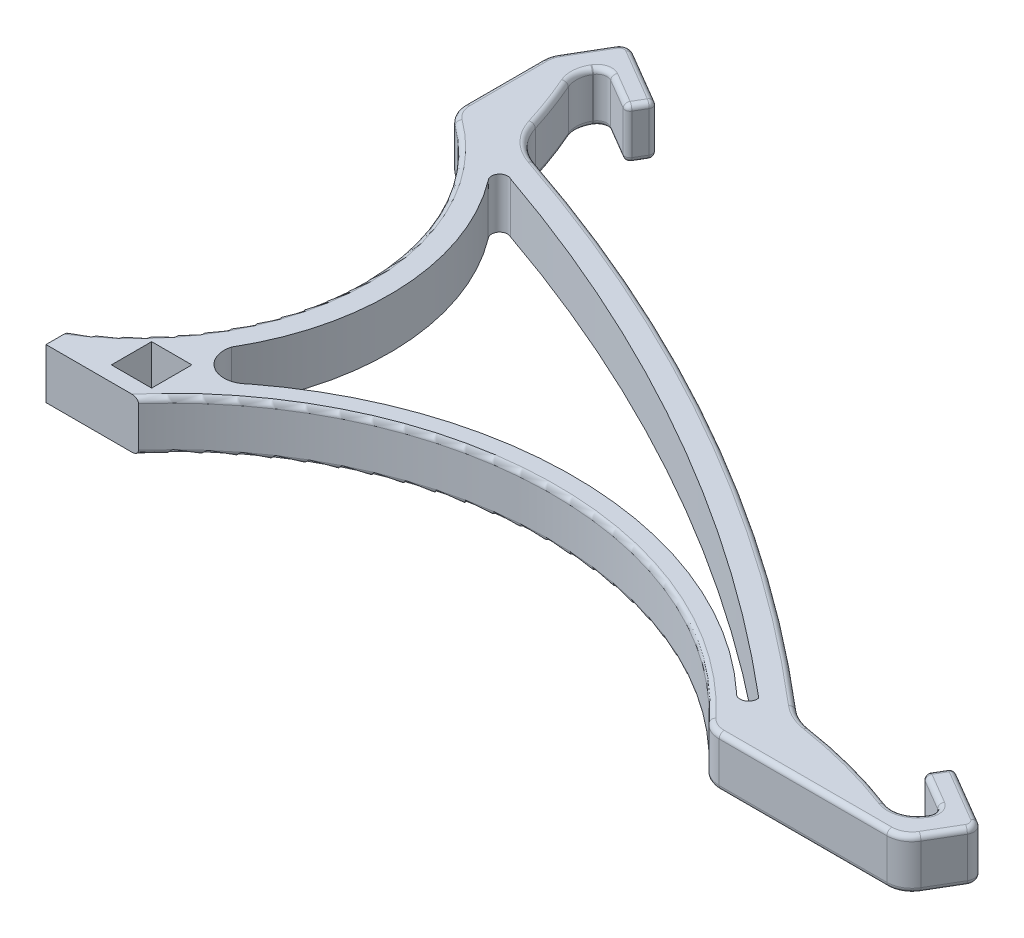
SolidWorks part; units mm, degrees
ref_plane "Front Plane" through (0, 0, 0) normal (0, 0, 1) x (1, 0, 0)
ref_plane "Top Plane" through (0, 0, 0) normal (0, 1, 0) x (1, 0, 0)
ref_plane "Right Plane" through (0, 0, 0) normal (1, 0, 0) x (0, 0, -1)
sketch "Sketch1" plane through (0, 0, 0) normal (0, 1, 0) x (1, 0, 0)
  line L0 (-82.5, 52.5) -> (87.5, -47.5)
  line L2 (-82.5, 52.5) -> (-82.5, -47.5)
  line L3 (-82.5, -47.5) -> (87.5, -47.5)
  point P0 (0, 0)
  dimension "D1" = 170
  dimension "D2" = 100
extrude "Boss-Extrude1" add sketch "Sketch1" along normal blind 10
sketch "Sketch2" plane through (0, 10, 0) normal (0, 1, 0) x (1, 0, 0)
  line L0 (28.4245, 45.2593) -> (-47.6285, -84.0308) construction
  line L1 (-7.5, -97.5) -> (-7.5, 22.4346) construction
  line L2 (-107.5, -4.7657) -> (210.8168, -7.7793) construction
  line L3 (-72.5, 46.6176) -> (-72.5, 42.261)
  line L4 (87.5, -47.5) -> (-82.5, 52.5) construction
  line L5 (70.501, -37.5006) -> (60.6028, -37.4952)
  line L6 (-82.5, -47.5) -> (87.5, -47.5) construction
  line L8 (-82.5, 52.5) -> (-82.5, -47.5) construction
  line L11 (70.501, -37.5006) -> (-72.5, 46.6176)
  line L12 (49.1121, -47.5) -> (-64.1121, -47.5)
  line L13 (-82.5, -42.735) -> (-82.5, 33.2036)
  arc A0 (-65.6807, 32.7803) -> (-72.5, 42.261) centre (-62.5, 42.261) cw
  arc A1 (54.1101, -35.0961) -> (60.6028, -37.4952) centre (60.6083, -27.4952) ccw
  arc A2 (-54.7539, -22.0523) -> (-51.8167, -24.3855) centre (-52.8534, -22.6752) ccw
  arc A5 (-55.6068, -34.1618) -> (-63.6168, -29.4695) centre (-59.0265, -30.8165) cw
  arc A6 (49.1121, -47.5) -> (-64.1121, -47.5) centre (-7.5, -97.5) ccw
  arc A7 (-82.5, -42.735) -> (-82.5, 33.2036) centre (-107.5, -4.7657) ccw
  arc A11 (49.1744, -37.4931) -> (46.162, -38.8845) centre (47.5173, -37.8621) cw
  arc A12 (54.1101, -35.0961) -> (-65.6807, 32.7803) centre (-180.5315, -309.5568) ccw
  arc A14 (-64.8707, 27.2014) -> (-66.8024, 24.71) centre (-65.6394, 25.8028) ccw
  arc A15 (49.1744, -37.4931) -> (-64.8707, 27.2014) centre (-180.5315, -309.5568) ccw
  arc A16 (-66.8024, 24.71) -> (-63.6168, -29.4695) centre (-105.788, -4.7657) cw
  arc A17 (-55.6068, -34.1618) -> (46.162, -38.8845) centre (-7.5, -96.3777) cw
  point P2 (54.1121, -47.5)
  point P3 (-69.1121, -47.5)
  point P9 (-82.5, 38.2036)
  point P25 (-82.5, -47.735)
  dimension "D1" = 5
  dimension "D2" = 5
  dimension "D3" = 2
  dimension "D4" = 90
  dimension "D11" = 10
  dimension "D5" = 97.95
  dimension "D6" = 100
  dimension "D7" = 50
  dimension "D8" = 5
  dimension "D9" = 5
extrude "Cut-Extrude1" cut sketch "Sketch2" against normal through all
sketch "Sketch3" plane through (0, 10, 0) normal (0, 1, 0) x (1, 0, 0)
  line L0 (87.5, -47.5) -> (92.3674, -39.2254)
  line L1 (-82.5, 52.5) -> (-77.6133, 60.8074)
  line L2 (87.5, -47.5) -> (70.501, -37.5006) construction
  line L3 (91.6576, -36.4875) -> (81.3144, -30.4033)
  line L4 (78.6778, -32.913) -> (79.9454, -30.7582)
  line L5 (-74.8754, 61.5172) -> (-64.5322, 55.4329)
  line L6 (79.0328, -34.282) -> (85.0663, -37.8311)
  line L7 (85.7761, -40.569) -> (83.1903, -44.9649)
  line L8 (83.1903, -44.9649) -> (87.5, -47.5)
  line L9 (-64.1773, 54.064) -> (-65.4448, 51.9092)
  line L10 (-66.8138, 51.5542) -> (-72.8473, 55.1034)
  line L11 (-75.5852, 54.3936) -> (-78.1903, 49.9649)
  line L12 (-72.5, 46.6176) -> (-82.5, 52.5) construction
  line L13 (-78.1903, 49.9649) -> (-82.5, 52.5)
  arc A0 (92.3674, -39.2254) -> (91.6576, -36.4875) centre (90.6435, -38.2114) ccw
  arc A1 (85.0663, -37.8311) -> (85.7761, -40.569) centre (84.0523, -39.555) cw
  arc A2 (79.0328, -34.282) -> (78.6778, -32.913) centre (79.5398, -33.4201) cw
  arc A3 (81.3144, -30.4033) -> (79.9454, -30.7582) centre (80.8073, -31.2652) ccw
  arc A4 (-72.8473, 55.1034) -> (-75.5852, 54.3936) centre (-73.8614, 53.3795) ccw
  arc A5 (-77.6133, 60.8074) -> (-74.8754, 61.5172) centre (-75.8895, 59.7933) cw
  arc A6 (-64.5322, 55.4329) -> (-64.1773, 54.064) centre (-65.0392, 54.571) cw
  arc A7 (-65.4448, 51.9092) -> (-66.8138, 51.5542) centre (-66.3068, 52.4162) cw
  point P11 (93.3814, -37.5016)
  point P20 (80.4524, -29.8963)
  point P32 (-76.5993, 62.5312)
  point P35 (-63.6703, 54.9259)
  point P38 (-65.9519, 51.0472)
  dimension "D5" = 2
  dimension "D6" = 1
  dimension "D22" = 2
  dimension "D23" = 1
  dimension "D1" = 90
  dimension "D2" = 90
  dimension "D3" = 5.1
  dimension "D4" = 15
  dimension "D7" = 5
  dimension "D8" = 90
  dimension "D9" = 90
  dimension "D10" = 90
  dimension "D11" = 90
  dimension "D12" = 90
  dimension "D13" = 90
  dimension "D14" = 90
  dimension "D15" = 90
  dimension "D16" = 90
  dimension "D17" = 90
  dimension "D18" = 5.138
  dimension "D19" = 15
  dimension "D20" = 2.5
  dimension "D21" = 5
  dimension "D24" = 2.5
extrude "Boss-Extrude3" add sketch "Sketch3" against normal through all
fillet "Fillet1" radius 5 6 edges at (83.1903, 5, 44.9649) (87.5, 5, 47.5) (49.1121, 5, 47.5) (-82.5, 5, -33.2036) (-82.5, 5, -52.5) (-78.1903, 5, -49.9649)
fillet "Fillet3" radius 100 2 edges at (-72.5, 5, -46.6176) (70.501, 5, 37.5006)
sketch "Sketch4" plane through (0, 10, 0) normal (0, 1, 0) x (1, 0, 0)
  line L1 (-64.5, -36.5) -> (-72.5, -36.5)
  line L2 (-72.5, -36.5) -> (-72.5, -44.5)
  line L3 (-72.5, -44.5) -> (-64.5, -44.5)
  line L4 (-64.5, -44.5) -> (-64.5, -36.5)
  line L6 (-82.5, -42.735) -> (-82.5, -47.5) construction
  line L8 (-82.5, -47.5) -> (-64.1121, -47.5) construction
  circle A0 centre (-68.5, -40.5) radius 4 construction
  dimension "D1" = 14
  dimension "D2" = 7
  dimension "D3" = 8
extrude "Cut-Extrude2" cut sketch "Sketch4" against normal through all
fillet "Fillet4" radius 1 62 edges at (-74.3633, 10, -55.3155) (-69.8306, 10, -53.3288) (-66.0558, 10, -51.4482) (-64.8111, 10, -52.9866) (-64.0712, 10, -54.822) (-69.7038, 10, -58.4751) (-76.3914, 10, -61.7293) (-79.7115, 10, -57.2405) (-75.6202, 10, -54.3341) (-8.571, 10, 21.9766) (90.6587, 10, 42.1303) (87.1227, 10, 46.8402) (49.3331, 10, 47.0866) (-82.3243, 10, -52.4522) (-81.9645, 10, -33.5573) (90.6587, 0, 42.1303) (-8.571, 0, 21.9766) (-75.6202, 0, -54.3341) (87.1227, 0, 46.8402) (49.3331, 0, 47.0866) (-82.3243, 0, -52.4522) (-81.9645, 0, -33.5573) (-76.3365, 0, -52.0404) (83.0714, 10, 42.838) (-76.3365, 10, -52.0404) (69.5123, 10, 39.5401) (-73.8458, 10, -44.5775) (83.0714, 0, 42.838) (69.5123, 0, 39.5401) (-73.8458, 0, -44.5775) (-62.0562, 0, 6.002) (-62.0562, 10, 6.002) (-2.5201, 10, -4.6045) (-69.6546, 10, -35.2745) (56.4458, 0, 36.5876) (-2.5201, 0, -4.6045) (-69.6546, 0, -35.2745) (56.4458, 10, 36.5876) (85.7508, 0, 40.6121) (85.9883, 0, 39.0531) (82.0495, 0, 36.0566) (78.5718, 0, 33.671) (79.3116, 0, 31.8356) (80.5564, 0, 30.2972) (86.486, 0, 33.4454) (92.5795, 0, 37.7095) (92.5795, 10, 37.7095) (86.486, 10, 33.4454) (80.5564, 10, 30.2972) (79.3116, 10, 31.8356) (78.5718, 10, 33.671) (82.0495, 10, 36.0566) (85.9883, 10, 39.0531) (85.7508, 10, 40.6121) (-79.7115, 0, -57.2405) (-76.3914, 0, -61.7293) (-69.7038, 0, -58.4751) (-64.0712, 0, -54.822) (-64.8111, 0, -52.9866) (-66.0558, 0, -51.4482) (-69.8306, 0, -53.3288) (-74.3633, 0, -55.3155)
